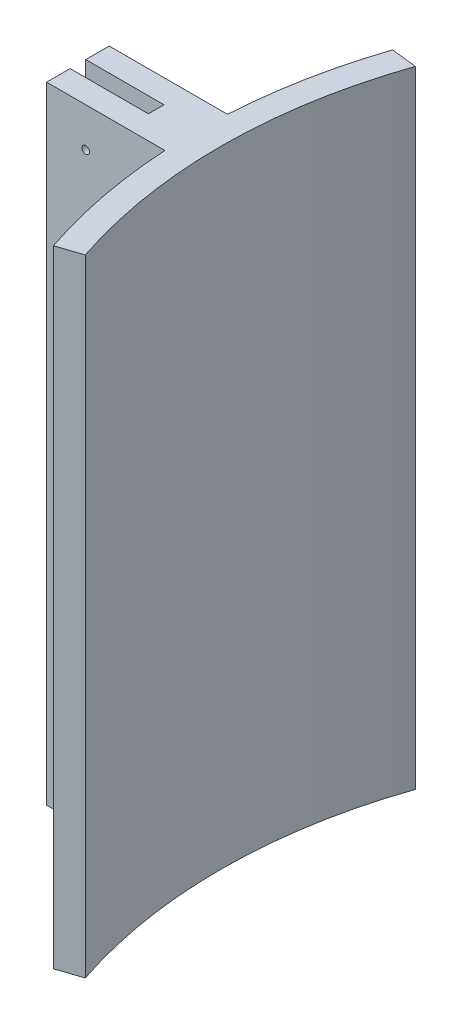
SolidWorks part; units mm, degrees
ref_plane "Front Plane" through (0, 0, 0) normal (0, 0, 1) x (1, 0, 0)
ref_plane "Top Plane" through (0, 0, 0) normal (0, 1, 0) x (1, 0, 0)
ref_plane "Right Plane" through (0, 0, 0) normal (1, 0, 0) x (0, 0, -1)
sketch "Sketch1" plane through (0, 0, 0) normal (0, 1, 0) x (1, 0, 0)
  line L0 (-65, 0) -> (0, 0) construction
  line L5 (-61.6337, -20.6469) -> (-64.6895, -21.6706)
  line L6 (-61.4089, 21.3061) -> (-64.6895, 21.6706)
  line L7 (0, 0) -> (-80.1235, 0) construction
  line L8 (-68.2228, -4) -> (-68.1054, -4)
  line L11 (-68.2228, -4) -> (-83.2228, -4)
  line L12 (-83.2228, 4) -> (-83.2228, 1)
  line L13 (-68.2228, 4) -> (-68.1054, 4)
  line L14 (-68.2228, 4) -> (-83.2228, 4)
  line L15 (-83.2228, 1) -> (-73.2228, 1)
  line L16 (-83.2228, -1) -> (-73.2228, -1)
  line L17 (-73.2228, -1) -> (-73.2228, 1)
  line L18 (-83.2228, -1) -> (-83.2228, -4)
  arc A0 (-61.6337, -20.6469) -> (-61.4089, 21.3061) centre (0, 0) cw
  arc A1 (-64.6895, -21.6706) -> (-68.1054, -4) centre (0, 0) cw
  arc A2 (-68.1054, 4) -> (-64.6895, 21.6706) centre (0, 0) cw
  dimension "D1" = 15
  dimension "D2" = 10
extrude "Boss-Extrude1" add sketch "Sketch1" along normal blind 80
sketch "Sketch9" plane through (0, 0, 4) normal (0, 0, 1) x (1, 0, 0)
  line L0 (-78.2228, 80) -> (-78.2228, 0) construction
  line L1 (-83.2228, 80) -> (-68.1054, 80) construction
  line L2 (-78.2228, 75) -> (-83.2228, 75) construction
  line L3 (-78.2228, 40) -> (-83.2228, 40) construction
  line L4 (-78.2228, 5) -> (-83.2228, 5) construction
  line L5 (-83.2228, 0) -> (-68.1054, 0) construction
  line L6 (-83.2228, 80) -> (-83.2228, 0) construction
  point P12 (0, 0)
  point P15 (-83.2228, 75)
  point P16 (-83.2228, 40)
  point P17 (-83.2228, 5)
  dimension "D1" = 80
  dimension "D2" = 5
  dimension "D3" = 5
  dimension "D4" = 5
hole_wizard "M1.2x0.25 Tapped Hole2" positions "Sketch10" profile "Sketch11" tap size "M1.2x0.25" standard "ANSI Metric" end condition through all
sketch "Sketch10" plane through (0, 0, 4) normal (0, 0, 1) x (1, 0, 0)
  point P0 (-78.2228, 75)
  point P3 (-78.2228, 40)
  point P7 (-78.2228, 5)
sketch "Sketch11" plane through (-78.2228, 75, 4) normal (1, 0, 0) x (0, -1, 0)
  line L0 (0, 0) -> (0, 25.6706)
  line L1 (0, 25.6706) -> (0.475, 25.6706)
  line L2 (0.475, 25.6706) -> (0.475, 0)
  line L5 (0.475, 0) -> (0, 0)
  line L11 (0, -6.35) -> (0, 107.95) construction
  dimension "Thru Tap Drill Dia." = 0.95
  dimension "Thru Tap Drill Depth" = 25.6706
cosmetic thread "Hole Thread4" parameters "D2"=1.2
cosmetic thread "Hole Thread5" parameters "D2"=1.2
cosmetic thread "Hole Thread6" parameters "D2"=1.2
